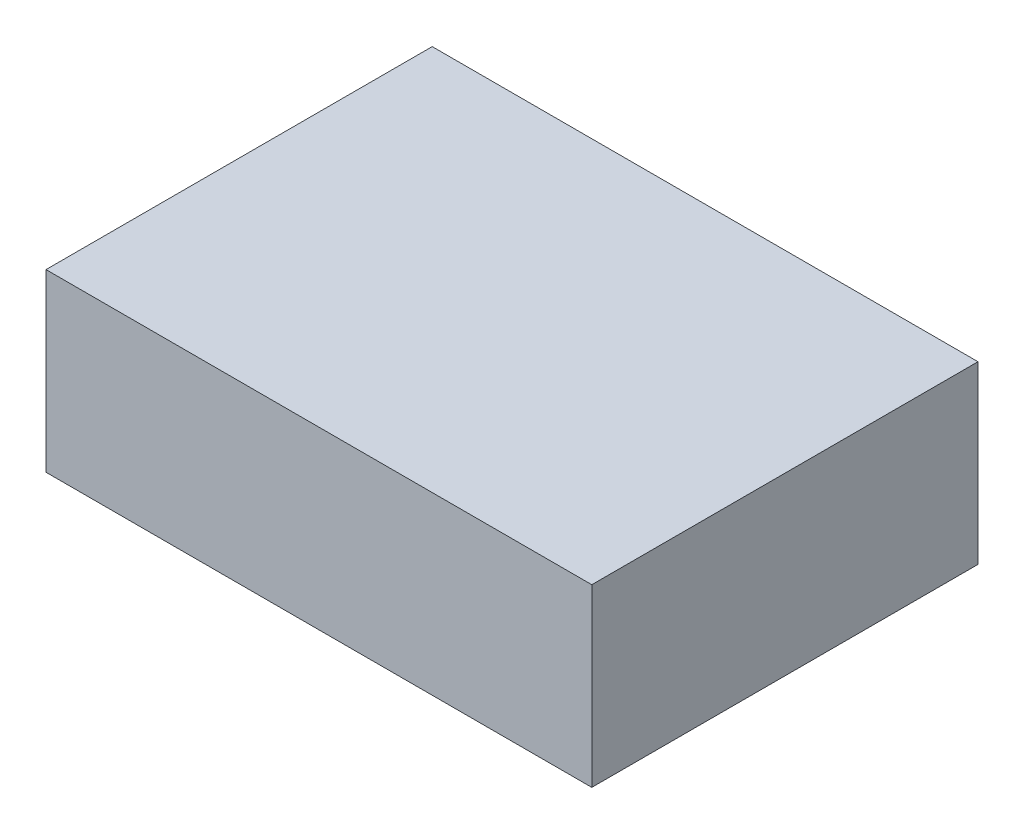
SolidWorks part; units mm, degrees
ref_plane "Front Plane" through (0, 0, 0) normal (0, 0, 1) x (1, 0, 0)
ref_plane "Top Plane" through (0, 0, 0) normal (0, 1, 0) x (1, 0, 0)
ref_plane "Right Plane" through (0, 0, 0) normal (1, 0, 0) x (0, 0, -1)
sketch "Sketch1" plane through (0, 0, 0) normal (0, 1, 0) x (1, 0, 0)
  line L1 (-85.5, -60.5) -> (85.5, -60.5)
  line L2 (-85.5, -60.5) -> (-85.5, 60.5)
  line L3 (-85.5, 60.5) -> (85.5, 60.5)
  line L4 (85.5, -60.5) -> (85.5, 60.5)
  line L5 (-85.5, -60.5) -> (85.5, 60.5) construction
  line L6 (-85.5, 60.5) -> (85.5, -60.5) construction
  point P0 (0, 0)
  dimension "D1" = 171
  dimension "D2" = 121
extrude "Boss-Extrude1" add sketch "Sketch1" along normal blind 55
